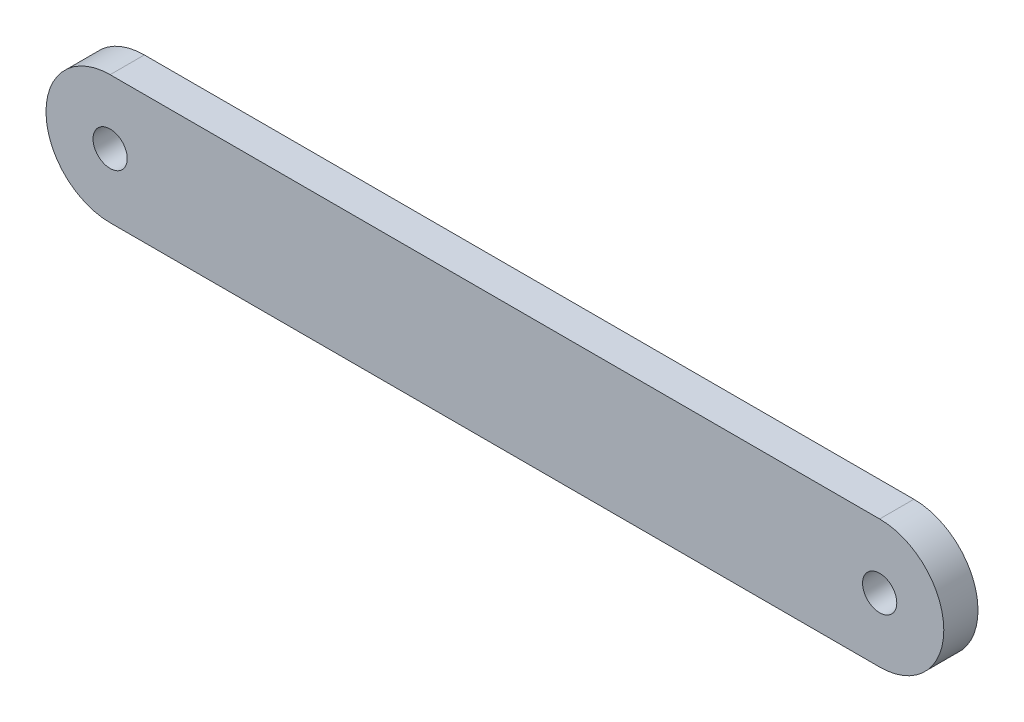
SolidWorks part; units mm, degrees
material "Pine"
ref_plane "Front Plane" through (0, 0, 0) normal (0, 0, 1) x (1, 0, 0)
ref_plane "Top Plane" through (0, 0, 0) normal (0, 1, 0) x (1, 0, 0)
ref_plane "Right Plane" through (0, 0, 0) normal (1, 0, 0) x (0, 0, -1)
sketch "Sketch1" plane through (0, 0, 0) normal (0, 0, 1) x (1, 0, 0)
  line L0 (0, 0) -> (90, 0) construction
  line L1 (0, 7.5) -> (90, 7.5)
  line L2 (0, -7.5) -> (90, -7.5)
  arc A0 (0, 7.5) -> (0, -7.5) centre (0, 0) ccw
  arc A1 (90, -7.5) -> (90, 7.5) centre (90, 0) ccw
  circle A2 centre (0, 0) radius 2
  circle A3 centre (90, 0) radius 2
  point P3 (45, 0)
  dimension "D1" = 4
  dimension "D2" = 15
  dimension "D3" = 90
extrude "Boss-Extrude1" add sketch "Sketch1" along normal blind 4
